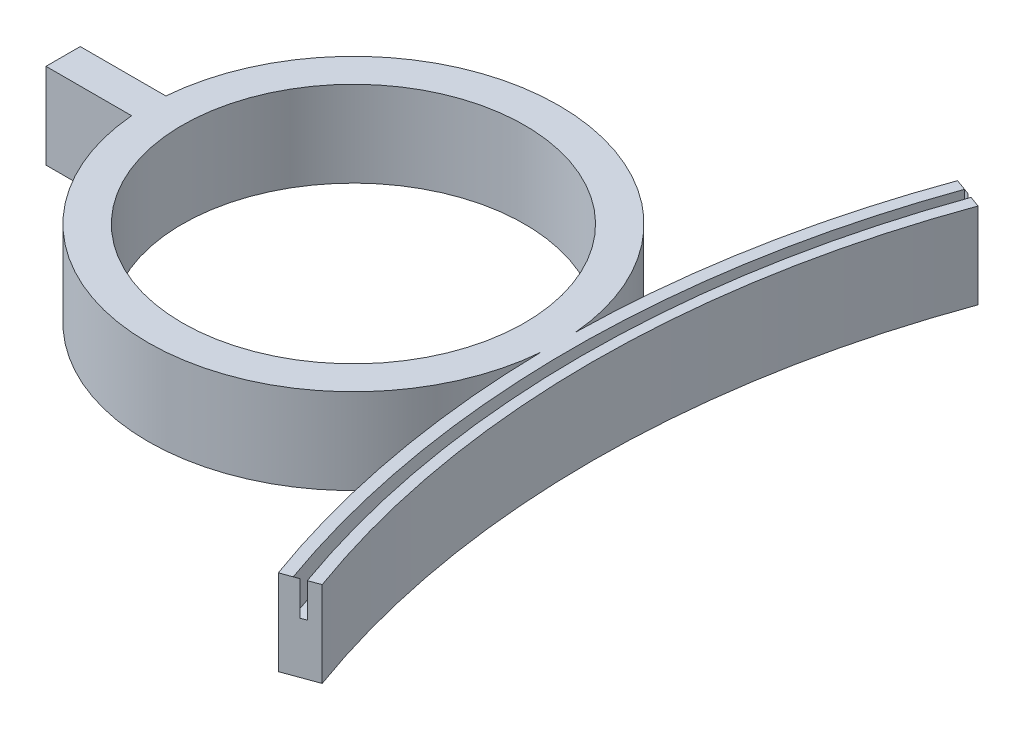
SolidWorks part; units mm, degrees
ref_plane "Front Plane" through (0, 0, 0) normal (0, 0, 1) x (1, 0, 0)
ref_plane "Top Plane" through (0, 0, 0) normal (0, 1, 0) x (1, 0, 0)
ref_plane "Right Plane" through (0, 0, 0) normal (1, 0, 0) x (0, 0, -1)
sketch "Sketch1" plane through (0, 0, 0) normal (0, 1, 0) x (1, 0, 0)
  line L0 (-21.537, 1.27) -> (-21.537, -1.27)
  line L1 (17.716, 0) -> (47.0886, 0) construction
  line L2 (19.6183, 25.1932) -> (22.0051, 24.3245)
  line L3 (19.6183, -25.1932) -> (22.0051, -24.3245)
  line L6 (-15.187, 1.27) -> (-21.537, 1.27)
  line L7 (-15.187, -1.27) -> (-21.537, -1.27)
  circle A0 centre (0, 0) radius 12.7
  arc A1 (22.0051, 24.3245) -> (22.0051, -24.3245) centre (88.836, 0) ccw
  arc A2 (19.6183, 25.1932) -> (15.187, 1.27) centre (88.836, 0) ccw
  arc A3 (15.187, 1.27) -> (-15.187, 1.27) centre (0, 0) ccw
  arc A4 (15.187, -1.27) -> (19.6183, -25.1932) centre (88.836, 0) ccw
  circle A5 centre (88.836, 0) radius 71.12 construction
  circle A6 centre (88.836, 0) radius 73.66 construction
  circle A7 centre (0, 0) radius 15.24 construction
  arc A8 (-15.187, -1.27) -> (15.187, -1.27) centre (0, 0) ccw
  point P3 (0, 0)
  point P8 (165.4337, 21.5361)
  point P17 (163.0047, 20.7935)
  point P23 (15.24, 0)
  dimension "D1" = 25.4
  dimension "D2" = 147.32
  dimension "D4" = 40
  dimension "D5" = 2.54
  dimension "D7" = 2.54
  dimension "D8" = 1.27
  dimension "D9" = 6.35
  dimension "D3" = 2.54
extrude "Boss-Extrude1" add sketch "Sketch1" along normal blind 6.35
sketch "Sketch2" plane through (0, 6.35, 0) normal (0, 1, 0) x (1, 0, 0)
  line L0 (22.0051, 24.3245) -> (19.6183, 25.1932) construction
  line L1 (19.6183, -25.1932) -> (22.0051, -24.3245) construction
  line L2 (20.429, 24.8956) -> (21.1944, 24.6221)
  line L3 (20.429, -24.8956) -> (21.1944, -24.6221)
  arc A0 (20.8117, 24.7588) -> (20.8117, -24.7588) centre (90.106, 0) ccw construction
  arc A1 (19.6183, 25.1932) -> (15.187, 1.27) centre (88.836, 0) ccw construction
  arc A2 (20.429, 24.8956) -> (20.429, -24.8956) centre (90.106, 0) ccw
  arc A3 (21.1944, 24.6221) -> (21.1944, -24.6221) centre (90.106, 0) ccw
  dimension "D1" = 1.27
  dimension "D2" = 0.4064
  dimension "D3" = 0.4064
extrude "Cut-Extrude1" cut sketch "Sketch2" against normal blind 2.54
